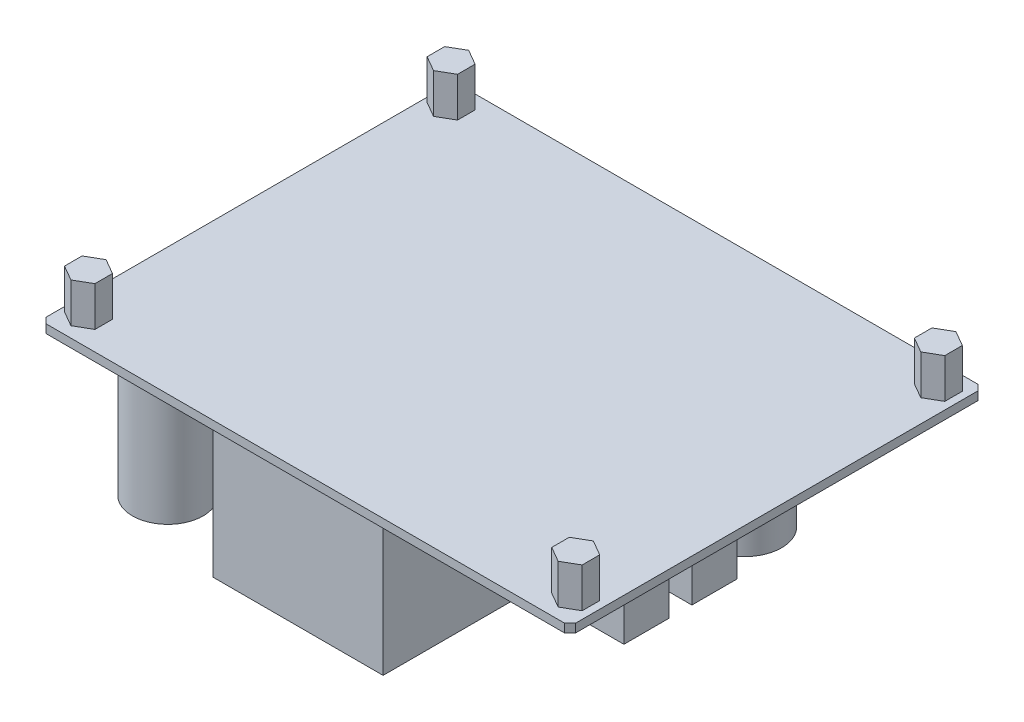
SolidWorks part; units mm, degrees
ref_plane "Спереди" through (0, 0, 0) normal (0, 0, 1) x (1, 0, 0)
ref_plane "Сверху" through (0, 0, 0) normal (0, 1, 0) x (1, 0, 0)
ref_plane "Справа" through (0, 0, 0) normal (1, 0, 0) x (0, 0, -1)
sketch "Эскиз1" plane through (0, 0, 0) normal (0, 1, 0) x (1, 0, 0)
  line L1 (-46.75, 36.5) -> (46.75, 36.5)
  line L2 (-46.75, 36.5) -> (-46.75, -36.5)
  line L3 (-46.75, -36.5) -> (46.75, -36.5)
  line L4 (46.75, 36.5) -> (46.75, -36.5)
  line L5 (-46.75, 36.5) -> (46.75, -36.5) construction
  line L6 (-46.75, -36.5) -> (46.75, 36.5) construction
  point P0 (0, 0)
  dimension "D1" = 73
  dimension "D2" = 93.5
extrude "Бобышка-Вытянуть1" add sketch "Эскиз1" along normal blind 1.5
chamfer "Фаска1" distance 1 angle 45 4 edges at (-46.75, 0.75, 36.5) (46.75, 0.75, 36.5) (46.75, 0.75, -36.5) (-46.75, 0.75, -36.5)
sketch "Эскиз2" plane through (0, 1.5, 0) normal (0, 1, 0) x (1, 0, 0)
  line L0 (42.75, 35.6) -> (40.0653, 34.05)
  line L1 (-43.25, 35.6) -> (-45.9347, 34.05)
  line L2 (-45.9347, 34.05) -> (-45.9347, 30.95)
  line L3 (-45.9347, 30.95) -> (-43.25, 29.4)
  line L4 (-43.25, 29.4) -> (-40.5653, 30.95)
  line L5 (-40.5653, 30.95) -> (-40.5653, 34.05)
  line L6 (-40.5653, 34.05) -> (-43.25, 35.6)
  line L7 (40.0653, 34.05) -> (40.0653, 30.95)
  line L8 (40.0653, 30.95) -> (42.75, 29.4)
  line L9 (42.75, 29.4) -> (45.4347, 30.95)
  line L10 (45.4347, 30.95) -> (45.4347, 34.05)
  line L11 (45.4347, 34.05) -> (42.75, 35.6)
  line L12 (42.75, -28.4) -> (40.0653, -29.95)
  line L13 (40.0653, -29.95) -> (40.0653, -33.05)
  line L14 (40.0653, -33.05) -> (42.75, -34.6)
  line L15 (42.75, -34.6) -> (45.4347, -33.05)
  line L16 (45.4347, -33.05) -> (45.4347, -29.95)
  line L17 (45.4347, -29.95) -> (42.75, -28.4)
  line L18 (-43.25, -28.4) -> (-45.9347, -29.95)
  line L19 (-45.9347, -29.95) -> (-45.9347, -33.05)
  line L20 (-45.9347, -33.05) -> (-43.25, -34.6)
  line L21 (-43.25, -34.6) -> (-40.5653, -33.05)
  line L22 (-40.5653, -33.05) -> (-40.5653, -29.95)
  line L23 (-40.5653, -29.95) -> (-43.25, -28.4)
  line L24 (-46.75, 35.5) -> (-46.75, -35.5) construction
  line L25 (45.75, 36.5) -> (-45.75, 36.5) construction
  circle A0 centre (-43.25, 32.5) radius 3.1 construction
  point P30 (0, 0)
  point P31 (0, 0)
  point P32 (0, 0)
  dimension "D3" = 3.5
  dimension "D4" = 4
  dimension "D5" = 6.2
  dimension "D1" = 2
  dimension "D2" = 2
extrude "Бобышка-Вытянуть2" add sketch "Эскиз2" along normal blind 7
sketch "Эскиз3" plane through (0, 0, 0) normal (0, -1, 0) x (1, 0, 0)
  line L0 (-45.75, 36.5) -> (45.75, 36.5) construction
  line L1 (-17.75, 35) -> (12.25, 35)
  line L2 (-17.75, 35) -> (-17.75, 5)
  line L3 (-17.75, 5) -> (12.25, 5)
  line L4 (12.25, 35) -> (12.25, 5)
  line L5 (-17.75, 35) -> (12.25, 5) construction
  line L6 (-17.75, 5) -> (12.25, 35) construction
  line L7 (-46.75, -35.5) -> (-46.75, 35.5) construction
  point P0 (-2.75, 20)
  dimension "D1" = 30
  dimension "D2" = 30
  dimension "D3" = 16.5
  dimension "D4" = 44
extrude "Бобышка-Вытянуть3" add sketch "Эскиз3" along normal blind 24
sketch "Эскиз4" plane through (0, 0, 0) normal (0, -1, 0) x (1, 0, 0)
  line L0 (-46.75, -35.5) -> (-46.75, 35.5) construction
  line L1 (-45.75, 36.5) -> (45.75, 36.5) construction
  circle A0 centre (-31.25, 29.5) radius 6.25
  dimension "D1" = 12.5
  dimension "D2" = 15.5
  dimension "D3" = 7
extrude "Бобышка-Вытянуть4" add sketch "Эскиз4" along normal blind 21
sketch "Эскиз5" plane through (0, 0, 0) normal (0, -1, 0) x (1, 0, 0)
  line L0 (-46.75, -35.5) -> (-46.75, 35.5) construction
  line L1 (-45.75, 36.5) -> (45.75, 36.5) construction
  circle A0 centre (-28.75, 16.5) radius 6.25
  dimension "D1" = 12.5
  dimension "D2" = 18
  dimension "D3" = 20
extrude "Бобышка-Вытянуть5" add sketch "Эскиз5" along normal blind 21
sketch "Эскиз6" plane through (0, 0, 0) normal (0, -1, 0) x (1, 0, 0)
  line L0 (-46.75, -35.5) -> (-46.75, 35.5) construction
  line L1 (-45.75, 36.5) -> (45.75, 36.5) construction
  circle A0 centre (-30.75, 3.5) radius 6.25
  dimension "D1" = 12.5
  dimension "D2" = 16
  dimension "D3" = 33
extrude "Бобышка-Вытянуть6" add sketch "Эскиз6" along normal blind 21
sketch "Эскиз8" plane through (0, 0, 0) normal (0, -1, 0) x (1, 0, 0)
  line L0 (-46.75, -35.5) -> (-46.75, 35.5) construction
  line L1 (-45.25, 25.5) -> (-37.25, 25.5)
  line L2 (-45.25, 25.5) -> (-45.25, 17.5)
  line L3 (-45.25, 17.5) -> (-37.25, 17.5)
  line L4 (-37.25, 25.5) -> (-37.25, 17.5)
  line L5 (-45.25, 25.5) -> (-37.25, 17.5) construction
  line L6 (-45.25, 17.5) -> (-37.25, 25.5) construction
  line L7 (-45.25, 13.5) -> (-37.25, 13.5)
  line L8 (-45.25, 13.5) -> (-45.25, 5.5)
  line L9 (-45.25, 5.5) -> (-37.25, 5.5)
  line L10 (-37.25, 13.5) -> (-37.25, 5.5)
  line L11 (-45.25, 13.5) -> (-37.25, 5.5) construction
  line L12 (-45.25, 5.5) -> (-37.25, 13.5) construction
  line L13 (37.25, 25.5) -> (45.25, 25.5)
  line L14 (37.25, 25.5) -> (37.25, 17.5)
  line L15 (37.25, 17.5) -> (45.25, 17.5)
  line L16 (45.25, 25.5) -> (45.25, 17.5)
  line L17 (37.25, 25.5) -> (45.25, 17.5) construction
  line L18 (37.25, 17.5) -> (45.25, 25.5) construction
  line L19 (37.25, 13.5) -> (45.25, 13.5)
  line L20 (37.25, 13.5) -> (37.25, 5.5)
  line L21 (37.25, 5.5) -> (45.25, 5.5)
  line L22 (45.25, 13.5) -> (45.25, 5.5)
  line L23 (37.25, 13.5) -> (45.25, 5.5) construction
  line L24 (37.25, 5.5) -> (45.25, 13.5) construction
  line L25 (-45.75, 36.5) -> (45.75, 36.5) construction
  line L26 (46.75, 35.5) -> (46.75, -35.5) construction
  point P0 (-41.25, 21.5)
  point P5 (-41.25, 9.5)
  point P10 (41.25, 21.5)
  point P15 (41.25, 9.5)
  point P20 (0, 0)
  point P21 (0, 0)
  point P22 (0, 0)
  point P23 (-79.5929, -5.7011)
  point P24 (-79.4769, 5.4261)
  point P25 (-79.9406, -22.8555)
  point P26 (0, 0)
  point P29 (0, 0)
  point P32 (0, 0)
  point P33 (0, 0)
  dimension "D1" = 8
  dimension "D2" = 5.5
  dimension "D4" = 15
  dimension "D8" = 12
  dimension "D9" = 12
  dimension "D10" = 5.5
extrude "Бобышка-Вытянуть7" add sketch "Эскиз8" along normal blind 7.5
sketch "Эскиз9" plane through (0, 0, 0) normal (0, -1, 0) x (1, 0, 0)
  circle A0 centre (16.9177, -5.1605) radius 6.5
  circle A1 centre (24.9177, -16.1605) radius 6.5
  point P4 (0, 0)
  point P5 (0, 0)
  dimension "D1" = 13
  dimension "D2" = 8
  dimension "D3" = 11
extrude "Бобышка-Вытянуть9" add sketch "Эскиз9" along normal blind 20.5
sketch "Эскиз10" plane through (0, 0, 0) normal (0, -1, 0) x (1, 0, 0)
  line L0 (-46.75, -35.5) -> (-46.75, 35.5) construction
  line L1 (-35.15, -29.3076) -> (-12.65, -29.3076)
  line L2 (-35.15, -29.3076) -> (-35.15, -34.9076)
  line L3 (-35.15, -34.9076) -> (-12.65, -34.9076)
  line L4 (-12.65, -29.3076) -> (-12.65, -34.9076)
  line L5 (-35.15, -29.3076) -> (-12.65, -34.9076) construction
  line L6 (-35.15, -34.9076) -> (-12.65, -29.3076) construction
  line L7 (13.35, -29.3076) -> (35.85, -29.3076)
  line L8 (13.35, -29.3076) -> (13.35, -34.9076)
  line L9 (13.35, -34.9076) -> (35.85, -34.9076)
  line L10 (35.85, -29.3076) -> (35.85, -34.9076)
  line L11 (13.35, -29.3076) -> (35.85, -34.9076) construction
  line L12 (13.35, -34.9076) -> (35.85, -29.3076) construction
  point P0 (-23.9, -32.1076)
  point P5 (24.6, -32.1076)
  point P10 (0, 0)
  dimension "D1" = 5.6
  dimension "D2" = 22.5
  dimension "D3" = 26
  dimension "D4" = 11.6
extrude "Бобышка-Вытянуть10" add sketch "Эскиз10" along normal blind 10
